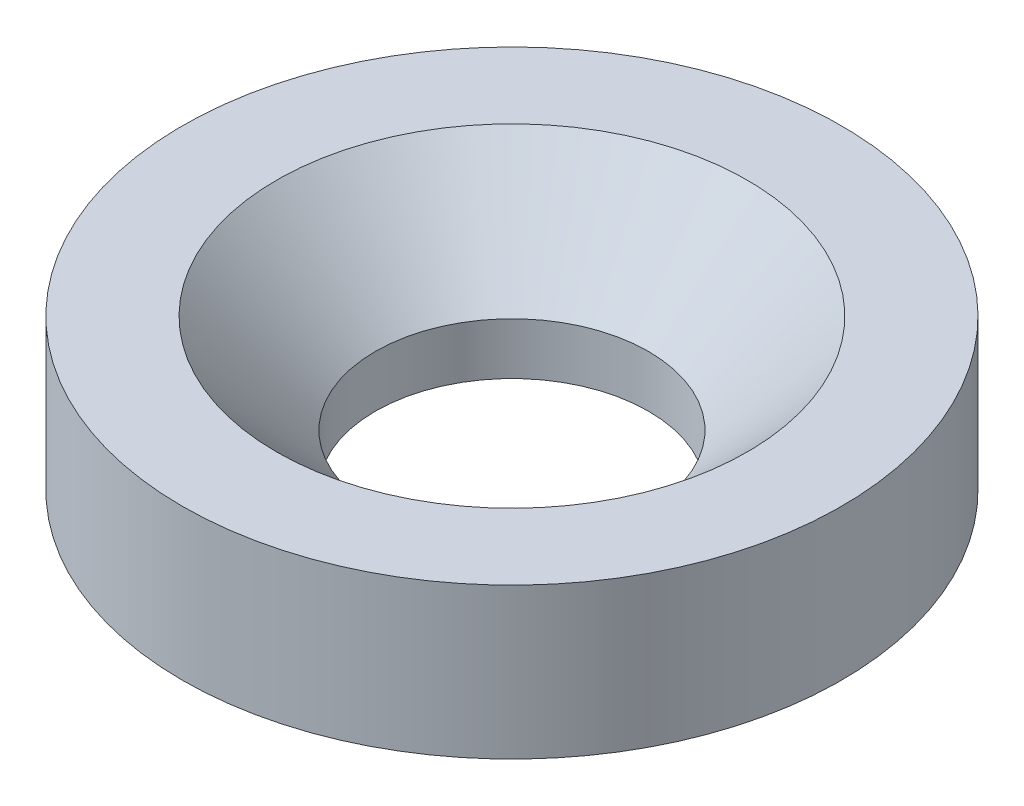
SolidWorks part; units mm, degrees
ref_plane "Front Plane" through (0, 0, 0) normal (0, 0, 1) x (1, 0, 0)
ref_plane "Top Plane" through (0, 0, 0) normal (0, 1, 0) x (1, 0, 0)
ref_plane "Right Plane" through (0, 0, 0) normal (1, 0, 0) x (0, 0, -1)
sketch "Sketch1" plane through (0, 0, 0) normal (0, 0, 1) x (1, 0, 0)
  line L0 (7.25, 0) -> (17.5, 0)
  line L1 (17.5, 0) -> (17.5, 8)
  line L2 (17.5, 8) -> (12.5, 8)
  line L3 (12.5, 8) -> (7.25, 2.75)
  line L4 (7.25, 2.75) -> (7.25, 0)
  line L5 (0, 16.992) -> (0, -10.1952) construction
  dimension "D1" = 17.5
  dimension "D2" = 8
  dimension "D3" = 7.25
  dimension "D4" = 12.5
  dimension "D5" = 45
revolve "Revolve1" add sketch "Sketch1" angle 360 about L5
